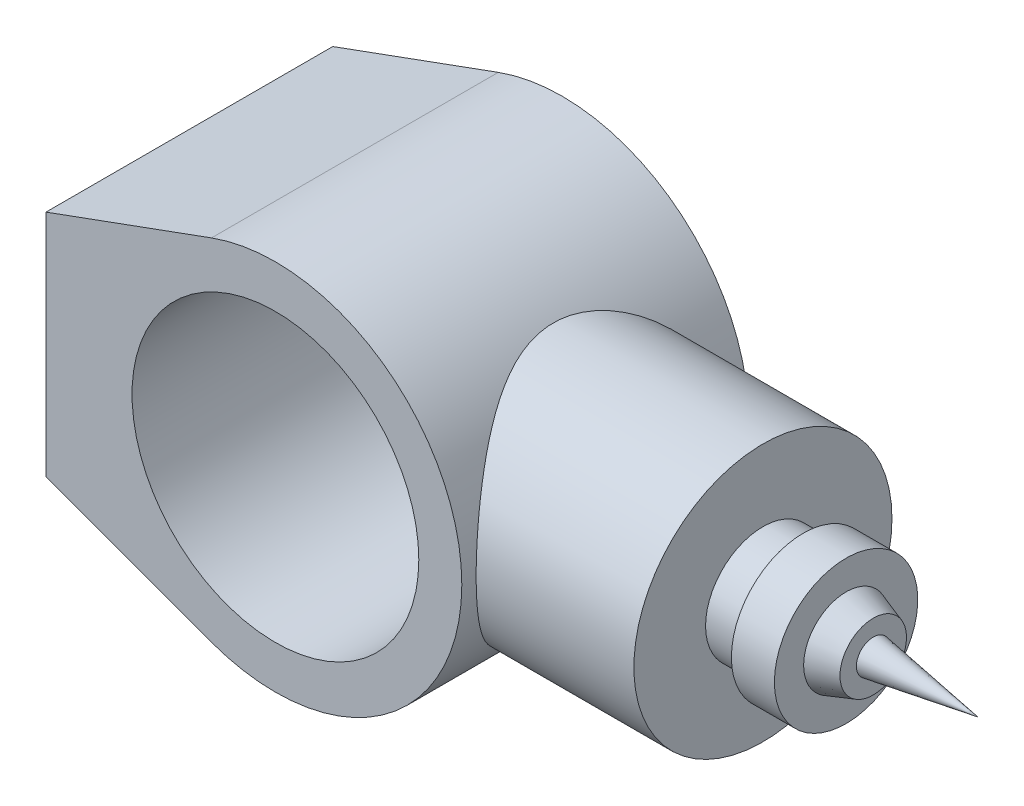
SolidWorks part; units mm, degrees
ref_plane "Front Plane" through (0, 0, 0) normal (0, 0, 1) x (1, 0, 0)
ref_plane "Top Plane" through (0, 0, 0) normal (0, 1, 0) x (1, 0, 0)
ref_plane "Right Plane" through (0, 0, 0) normal (1, 0, 0) x (0, 0, -1)
sketch "Sketch1" plane through (0, 0, 0) normal (0, 0, 1) x (1, 0, 0)
  line L0 (-80, 40) -> (-80, -40)
  line L1 (-80, 40) -> (-22.2817, 61.0617)
  line L2 (-80, -40) -> (-22.2817, -61.0617)
  arc A0 (-22.2817, -61.0617) -> (-22.2817, 61.0617) centre (0, 0) ccw
  circle A1 centre (0, 0) radius 50
  point P7 (-80, 0)
  dimension "D1" = 130
  dimension "D2" = 100
  dimension "D3" = 80
  dimension "D4" = 80
extrude "Boss-Extrude1" add sketch "Sketch1" along normal mid plane 100
ref_plane "Plane1" through (120, 0, 0) normal (1, 0, 0) x (0, 0, -1)
sketch "Sketch2" plane through (120, 0, 0) normal (1, 0, 0) x (0, 0, -1)
  circle A0 centre (0, 0) radius 45
  dimension "D1" = 90
extrude "Boss-Extrude2" add sketch "Sketch2" against normal up to next contours A0
sketch "Sketch3" plane through (0, 0, 0) normal (0, 0, 1) x (1, 0, 0)
  line L0 (0, 0) -> (194.6914, 0) construction
  line L1 (120, -20) -> (134, -20)
  line L2 (120, -55) -> (120, 55) construction
  line L3 (134, -20) -> (134, -25)
  line L4 (134, -25) -> (149, -25)
  line L5 (149, -25) -> (149, -14.8062)
  line L6 (149, -14.8062) -> (158.4705, -11.5954)
  line L7 (158.4705, -11.5954) -> (158.4705, -5.882)
  line L8 (158.4705, -5.882) -> (195, 0)
  line L9 (195, 0) -> (120, 0)
  line L10 (120, 0) -> (120, -20)
  dimension "D1" = 20
  dimension "D2" = 14
  dimension "D3" = 5
  dimension "D4" = 15
  dimension "D5" = 10.1938
  dimension "D6" = 10
  dimension "D7" = 37
  dimension "D8" = 75
revolve "Revolve1" add sketch "Sketch3" angle 360 about L0
